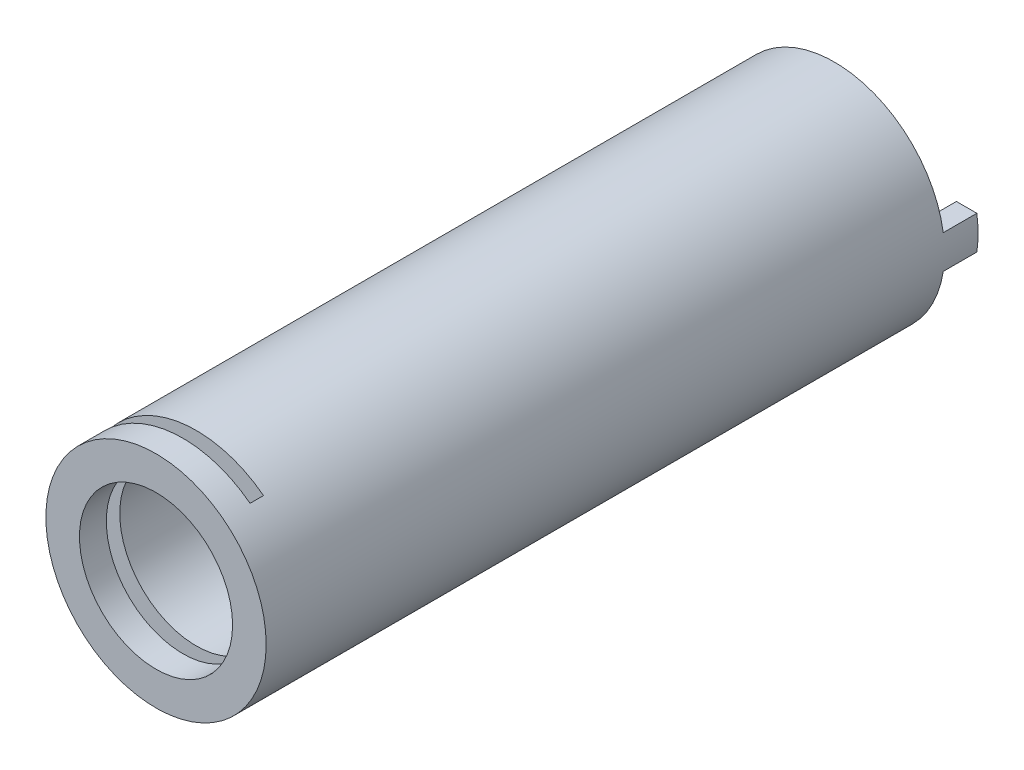
SolidWorks part; units mm, degrees
ref_plane "Front Plane" through (0, 0, 0) normal (0, 0, 1) x (1, 0, 0)
ref_plane "Top Plane" through (0, 0, 0) normal (0, 1, 0) x (1, 0, 0)
ref_plane "Right Plane" through (0, 0, 0) normal (1, 0, 0) x (0, 0, -1)
sketch "Sketch1" plane through (0, 0, 0) normal (0, 0, 1) x (1, 0, 0)
  circle A0 centre (0, 0) radius 11.4
  circle A1 centre (0, 0) radius 16.4
  dimension "D1" = 22.8
  dimension "D2" = 5
extrude "Boss-Extrude1" add sketch "Sketch1" along normal blind 101
sketch "Sketch2" plane through (0, 0, 0) normal (1, 0, 0) x (0, 0, -1)
  line L0 (-101, 16.4) -> (-101, -16.4) construction
  line L1 (-97, 25.5795) -> (-95, 25.5795)
  line L2 (-97, 25.5795) -> (-97, -23.9185)
  line L3 (-97, -23.9185) -> (-95, -23.9185)
  line L4 (-95, 25.5795) -> (-95, -23.9185)
  dimension "D1" = 2
  dimension "D2" = 4
extrude "Cut-Extrude1" cut sketch "Sketch2" against normal blind 100 and the other way blind 10.0001
sketch "Sketch3" plane through (0, 0, 0) normal (0, 0, -1) x (-1, 0, 0)
  line L0 (13.1647, 2.5) -> (16.2083, 2.5)
  line L1 (-16.2083, 2.5) -> (-13.1647, 2.5)
  line L3 (-16.2083, -2.5) -> (-13.1647, -2.5)
  line L5 (13.1647, -2.5) -> (16.2083, -2.5)
  line L6 (-16.4, 0) -> (-13.4, 0) construction
  arc A0 (-16.2083, 2.5) -> (-16.2083, -2.5) centre (0, 0) ccw
  arc A1 (-13.1647, 2.5) -> (-13.1647, -2.5) centre (0, 0) ccw
  arc A2 (16.2083, -2.5) -> (16.2083, 2.5) centre (0, 0) ccw
  arc A3 (13.1647, -2.5) -> (13.1647, 2.5) centre (0, 0) ccw
  circle A4 centre (0, 0) radius 16.4 construction
  point P14 (-12.8759, 0)
  dimension "D1" = 5
  dimension "D2" = 3
extrude "Boss-Extrude2" add sketch "Sketch3" along normal blind 5
